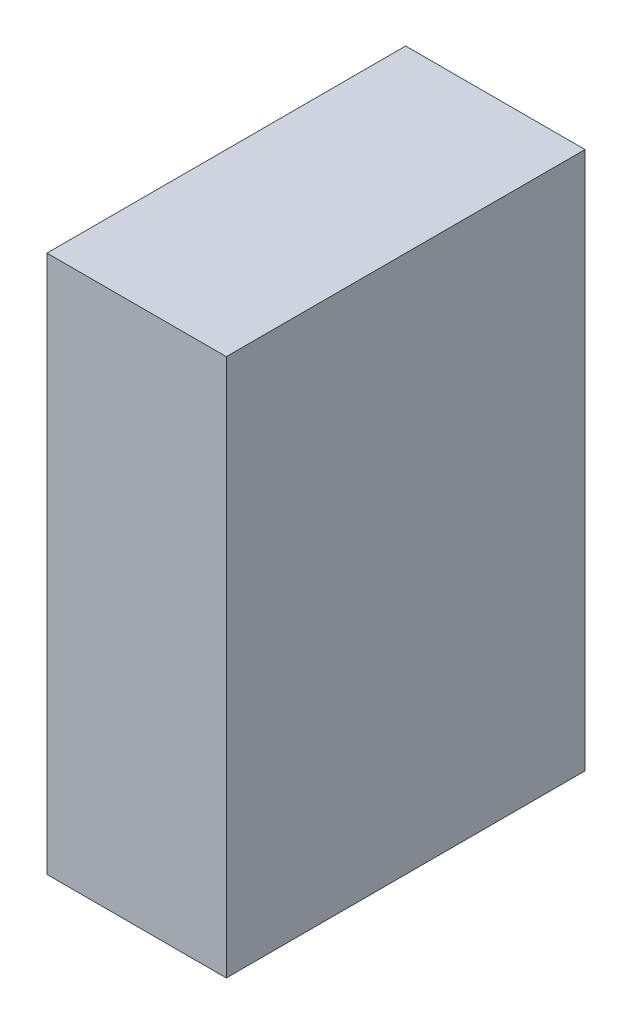
SolidWorks part; units mm, degrees
ref_plane "Front Plane" through (0, 0, 0) normal (0, 0, 1) x (1, 0, 0)
ref_plane "Top Plane" through (0, 0, 0) normal (0, 1, 0) x (1, 0, 0)
ref_plane "Right Plane" through (0, 0, 0) normal (1, 0, 0) x (0, 0, -1)
sketch "Sketch1" plane through (0, 0, 0) normal (0, 0, 1) x (1, 0, 0)
  line L1 (-12.5, -37.5) -> (12.5, -37.5)
  line L2 (-12.5, -37.5) -> (-12.5, 37.5)
  line L3 (-12.5, 37.5) -> (12.5, 37.5)
  line L4 (12.5, -37.5) -> (12.5, 37.5)
  line L5 (-12.5, -37.5) -> (12.5, 37.5) construction
  line L6 (-12.5, 37.5) -> (12.5, -37.5) construction
  point P0 (0, 0)
  dimension "D1" = 75
  dimension "D2" = 25
extrude "Boss-Extrude1" add sketch "Sketch1" along normal mid plane 50
